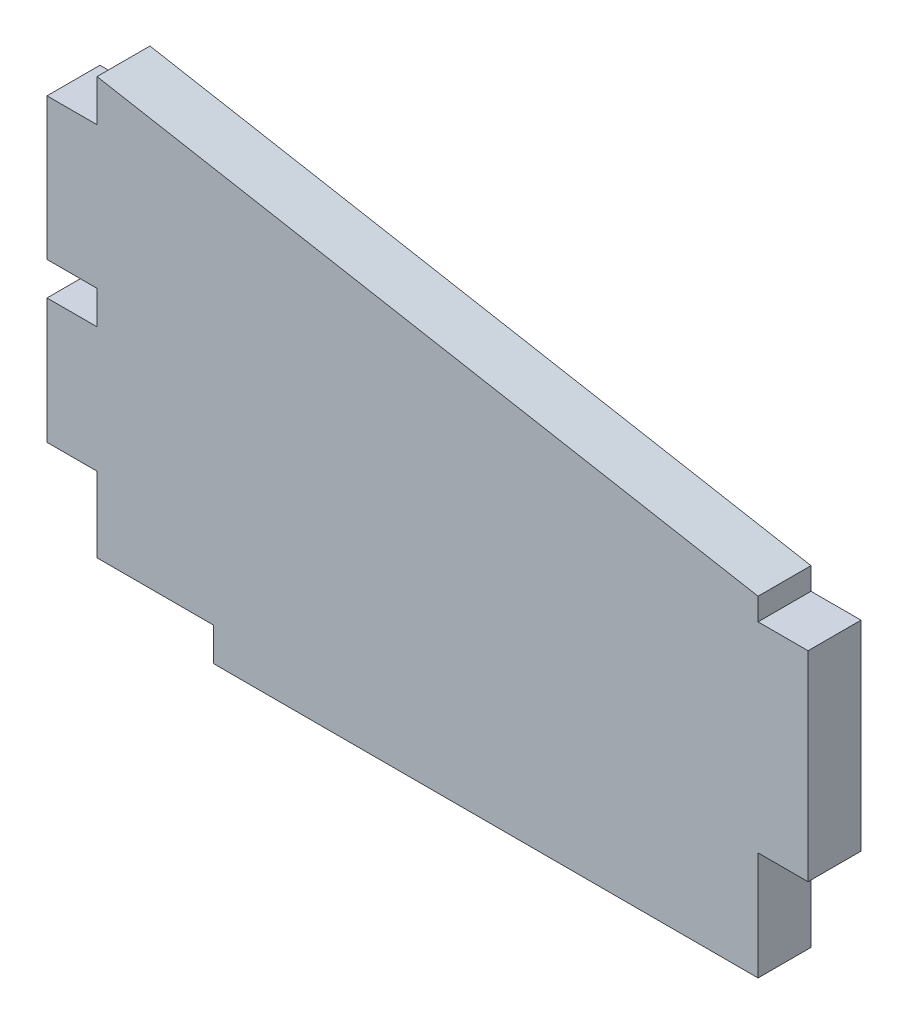
SolidWorks part; units mm, degrees
ref_plane "Front Plane" through (0, 0, 0) normal (0, 0, 1) x (1, 0, 0)
ref_plane "Top Plane" through (0, 0, 0) normal (0, 1, 0) x (1, 0, 0)
ref_plane "Right Plane" through (0, 0, 0) normal (1, 0, 0) x (0, 0, -1)
sketch "Sketch1" plane through (0, 0, 0) normal (0, 0, 1) x (1, 0, 0)
  line L0 (-19.825, 12.5) -> (19.825, 5.3317)
  line L1 (-19.825, -12.5) -> (19.825, -12.5)
  line L2 (-19.825, -12.5) -> (-19.825, 12.5)
  line L3 (-19.825, 12.5) -> (19.825, 12.5)
  line L4 (19.825, -12.5) -> (19.825, 12.5)
  line L5 (-19.825, -12.5) -> (19.825, 12.5) construction
  line L6 (-19.825, 12.5) -> (19.825, -12.5) construction
  line L7 (-19.825, -8) -> (-22.825, -8)
  line L8 (-19.825, -8) -> (-19.825, 10)
  line L9 (-19.825, 10) -> (-22.825, 10)
  line L10 (-22.825, -8) -> (-22.825, 10)
  line L11 (19.825, -8) -> (22.825, -8)
  line L12 (19.825, -8) -> (19.825, 4)
  line L13 (19.825, 4) -> (22.825, 4)
  line L14 (22.825, -8) -> (22.825, 4)
  point P0 (0, 0)
  dimension "D1" = 3
  dimension "D2" = 3
  dimension "D3" = 4.5
  dimension "D4" = 4.5
  dimension "D5" = 25
  dimension "D6" = 18
  dimension "D7" = 12
  dimension "D8" = 39.65
extrude "Boss-Extrude1" add sketch "Sketch1" along normal blind 3.175 contours L1 L4 L0 L2 | L11 L14 L13 L4 | L10 L7 L2 L9
sketch "Sketch2" plane through (0, 0, 3.175) normal (0, 0, 1) x (1, 0, 0)
  line L1 (19.825, -12.5) -> (-12.825, -12.5)
  line L2 (19.825, -12.5) -> (19.825, -14.5)
  line L3 (19.825, -14.5) -> (-12.825, -14.5)
  line L4 (-12.825, -12.5) -> (-12.825, -14.5)
  dimension "D1" = 32.65
  dimension "D2" = 2
extrude "Boss-Extrude2" add sketch "Sketch2" against normal up to surface (3.175 mm away) up to face at (0, -0.9307, 0)
sketch "Sketch3" plane through (0, 0, 3.175) normal (0, 0, 1) x (1, 0, 0)
  line L0 (-22.825, -8) -> (-22.825, 10) construction
  line L1 (-22.825, 1.5) -> (-19.825, 1.5)
  line L2 (-22.825, 1.5) -> (-22.825, -0.5)
  line L3 (-22.825, -0.5) -> (-19.825, -0.5)
  line L4 (-19.825, 1.5) -> (-19.825, -0.5)
  line L5 (-19.825, -8) -> (-22.825, -8) construction
  dimension "D1" = 3
  dimension "D2" = 7.5
  dimension "D3" = 2
extrude "Cut-Extrude1" cut sketch "Sketch3" against normal through all both contours L2 L1 L4 L3
